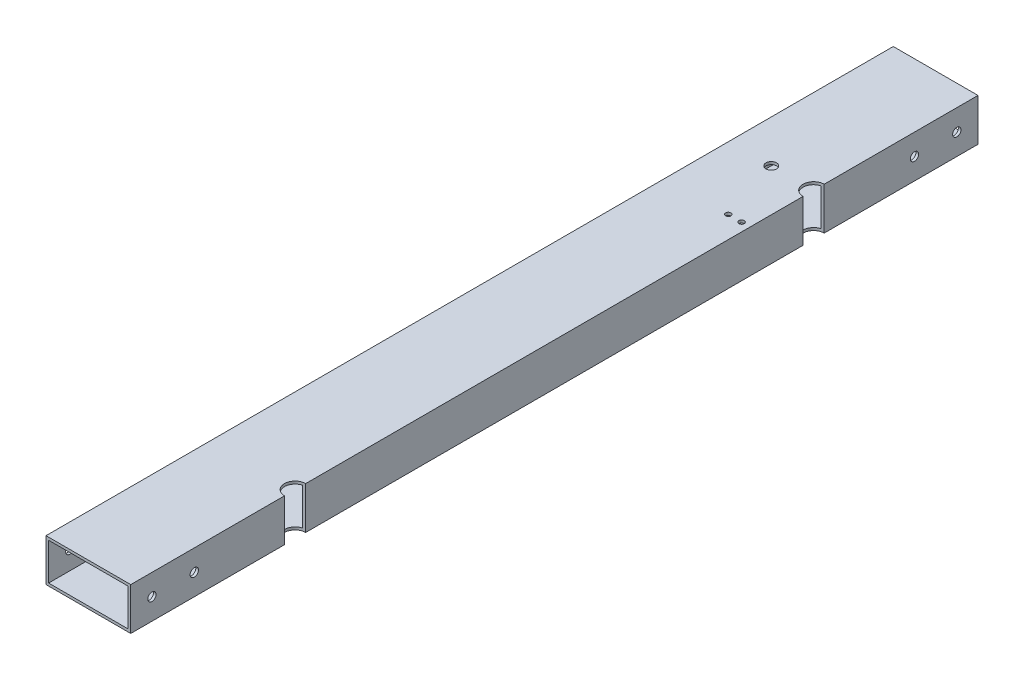
SolidWorks part; units mm, degrees
material "6061 Alloy"
ref_plane "Front Plane" through (0, 0, 0) normal (0, 0, 1) x (1, 0, 0)
ref_plane "Top Plane" through (0, 0, 0) normal (0, 1, 0) x (1, 0, 0)
ref_plane "Right Plane" through (0, 0, 0) normal (1, 0, 0) x (0, 0, -1)
sketch "Sketch1" plane through (0, 0, 0) normal (0, 0, 1) x (1, 0, 0)
  line L0 (-23.8125, 11.1125) -> (23.8125, 11.1125)
  line L2 (-25.4, 12.7) -> (25.4, 12.7)
  line L3 (-25.4, 12.7) -> (-25.4, -12.7)
  line L4 (-25.4, -12.7) -> (25.4, -12.7)
  line L5 (25.4, 12.7) -> (25.4, -12.7)
  line L10 (23.8125, 11.1125) -> (23.8125, -11.1125)
  line L11 (-23.8125, -11.1125) -> (23.8125, -11.1125)
  line L12 (-23.8125, 11.1125) -> (-23.8125, -11.1125)
  point P12 (0, 12.7)
  point P14 (25.4, 0)
  dimension "Wall Thickness" = 1.5875
  dimension "Outside Width" = 50.8
  dimension "Outside Height" = 25.4
  dimension "Inside Height" = 22.225
  dimension "Inside Width" = 47.625
sketch "Sketch2" plane through (0, 0, 0) normal (1, 0, 0) x (0, 0, -1)
  line L0 (254, 0) -> (-254, 0)
  point P4 (0, 0)
  point P7 (-254, 0)
  point P10 (254, 0)
  dimension "Length" = 508
sketch "Sketch3" plane through (0, 0, 0) normal (0, 0, 1) x (1, 0, 0)
  line L21 (25.4, 12.7) -> (-25.4, 12.7)
  line L22 (25.4, -12.7) -> (25.4, 12.7)
  line L23 (-25.4, -12.7) -> (25.4, -12.7)
  line L24 (-25.4, 12.7) -> (-25.4, -12.7)
  line L25 (25.4, 12.7) -> (-25.4, 12.7)
  line L26 (25.4, -12.7) -> (25.4, 12.7)
  line L27 (-25.4, -12.7) -> (25.4, -12.7)
  line L28 (-25.4, 12.7) -> (-25.4, -12.7)
  line L29 (23.8125, 11.1125) -> (-23.8125, 11.1125)
  line L30 (23.8125, -11.1125) -> (23.8125, 11.1125)
  line L31 (-23.8125, -11.1125) -> (23.8125, -11.1125)
  line L32 (-23.8125, 11.1125) -> (-23.8125, -11.1125)
  line L33 (23.8125, 11.1125) -> (-23.8125, 11.1125)
  line L34 (23.8125, -11.1125) -> (23.8125, 11.1125)
  line L35 (-23.8125, -11.1125) -> (23.8125, -11.1125)
  line L36 (-23.8125, 11.1125) -> (-23.8125, -11.1125)
  dimension "D1" = 0
  dimension "D2" = 0
extrude "Boss-Extrude1" add sketch "Sketch3" along normal up to vertex (254 mm away) and the other way up to vertex (254 mm away) up to point (0, 0, 254) other way up to point (0, 0, -254)
sketch "Drawing Reference" plane through (0, 0, 0) normal (1, 0, 0) x (0, 0, -1)
  line L0 (-254, 0) -> (254, 0) construction
  line L1 (0, -12.7) -> (0, 12.7) construction
  line L2 (-254, -12.7) -> (254, -12.7) construction
  line L5 (-254, 12.7) -> (254, 12.7) construction
  point P7 (-217.424, 0)
  point P8 (217.424, 0)
  dimension "D1" = 36.576
hole_wizard "#10 Clearance Hole1" positions "Sketch4" profile "Sketch5" hole size "#10" standard "ANSI Inch" end condition through all
sketch "Sketch4" plane through (25.4, 0, 0) normal (1, 0, 0) x (0, 0, -1)
  point P3 (-215.9, 0)
  point P12 (-241.3, 0)
  point P18 (215.9, 0)
  point P23 (241.3, 0)
sketch "Sketch5" plane through (25.4, 0, 215.9) normal (0, 1, 0) x (0, 0, -1)
  line L0 (0, 0) -> (0, 50.8)
  line L1 (0, 50.8) -> (2.4892, 50.8)
  line L2 (2.4892, 50.8) -> (2.4892, 0)
  line L5 (2.4892, 0) -> (0, 0)
  line L11 (0, -6.35) -> (0, 107.95) construction
  dimension "Thru Hole Dia." = 4.9784
  dimension "Thru Hole Depth" = 50.8
sketch "Sketch6" plane through (0, 12.7, 0) normal (0, 1, 0) x (1, 0, 0)
  line L0 (25.4, -254) -> (25.4, -155.448) construction
  line L1 (25.4, -254) -> (25.4, 254) construction
  line L2 (25.4, 0) -> (42.2258, 0) construction
  circle A0 centre (25.4, -155.448) radius 6.35
  circle A1 centre (25.4, 155.448) radius 6.35
  dimension "D1" = 98.552
extrude "Cut-Extrude1" cut sketch "Sketch6" against normal through all
sketch "Sketch7" plane through (0, 12.7, 0) normal (0, 1, 0) x (1, 0, 0)
  line L0 (25.4, 149.098) -> (25.4, 161.798) construction
  line L1 (25.4, 155.448) -> (0, 155.448) construction
  line L2 (25.4, 149.098) -> (25.4, 117.348) construction
  line L3 (25.4, -149.098) -> (25.4, 149.098) construction
  line L4 (25.4, 117.348) -> (20.32, 117.348) construction
  line L5 (20.32, 117.348) -> (12.32, 117.348) construction
  dimension "D3" = 31.75
  dimension "D4" = 5.08
hole_wizard "1/4 (0.25) Diameter Hole1" positions "Sketch8" profile "Sketch9" hole size "1/4" standard "ANSI Inch"
sketch "Sketch8" plane through (0, 12.7, 0) normal (0, 1, 0) x (1, 0, 0)
  point P0 (0, 155.448)
sketch "Sketch9" plane through (0, 12.7, -155.448) normal (1, 0, 0) x (0, 0, 1)
  line L0 (0, 0) -> (0, 6.9877)
  line L1 (0, 6.9877) -> (3.175, 5.08)
  line L2 (3.175, 5.08) -> (3.175, 0)
  line L5 (3.175, 0) -> (0, 0)
  line L10 (0, 6.9877) -> (-3.175, 5.08) construction
  line L11 (0, -6.35) -> (0, 107.95) construction
  dimension "Hole Dia." = 6.35
  dimension "Hole Depth" = 5.08
  dimension "Drill Angle" = 118
hole_wizard "Ø3.2 (3.2) Diameter Hole1" positions "Sketch10" profile "Sketch11" hole size "Ø3.2" standard "ANSI Metric" end condition through all
sketch "Sketch10" plane through (0, 12.7, 0) normal (0, 1, 0) x (1, 0, 0)
  point P0 (20.32, 117.348)
  point P3 (12.32, 117.348)
sketch "Sketch11" plane through (20.32, 12.7, -117.348) normal (1, 0, 0) x (0, 0, 1)
  line L0 (0, 0) -> (0, 25.4)
  line L1 (0, 25.4) -> (1.6, 25.4)
  line L2 (1.6, 25.4) -> (1.6, 0)
  line L5 (1.6, 0) -> (0, 0)
  line L11 (0, -6.35) -> (0, 107.95) construction
  dimension "Thru Hole Dia." = 3.2
  dimension "Thru Hole Depth" = 25.4
equation "\"D1@Drawing Reference\"=\"Outside Width@Sketch1\" * 0.72"
